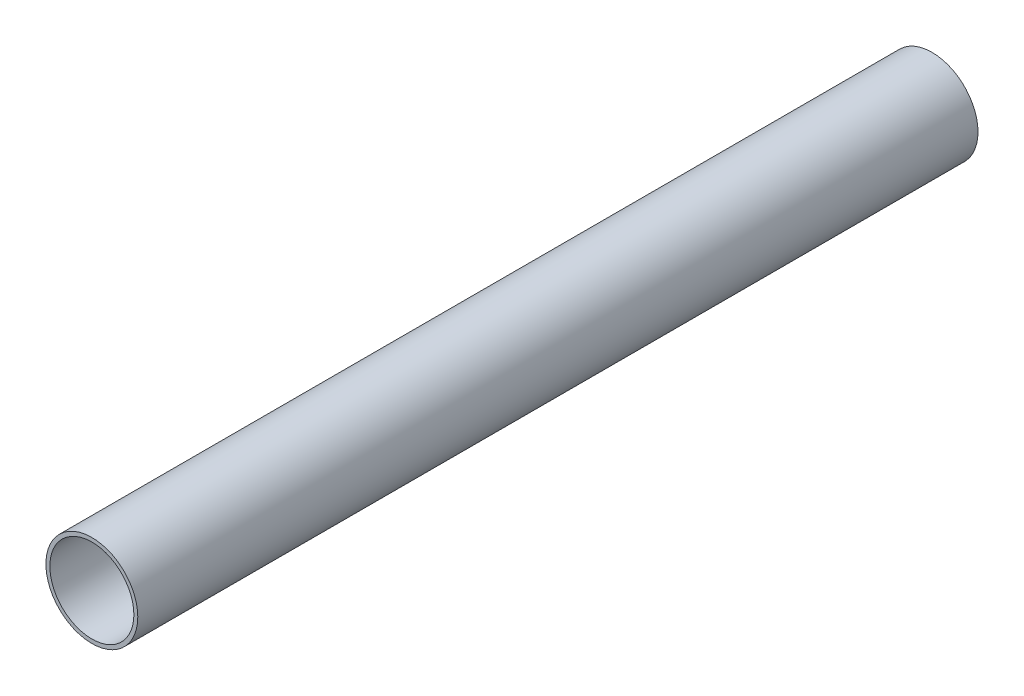
SolidWorks part; units mm, degrees
ref_plane "Alzado" through (0, 0, 0) normal (0, 0, 1) x (1, 0, 0)
ref_plane "Planta" through (0, 0, 0) normal (0, 1, 0) x (1, 0, 0)
ref_plane "Vista lateral" through (0, 0, 0) normal (1, 0, 0) x (0, 0, -1)
sketch "Croquis1" plane through (0, 0, 0) normal (0, 0, 1) x (1, 0, 0)
  circle A0 centre (0, 0) radius 109.35
  circle A1 centre (0, 0) radius 100
  dimension "D1" = 218.7
  dimension "D2" = 200
extrude "Saliente-Extruir1" add sketch "Croquis1" against normal blind 2000
